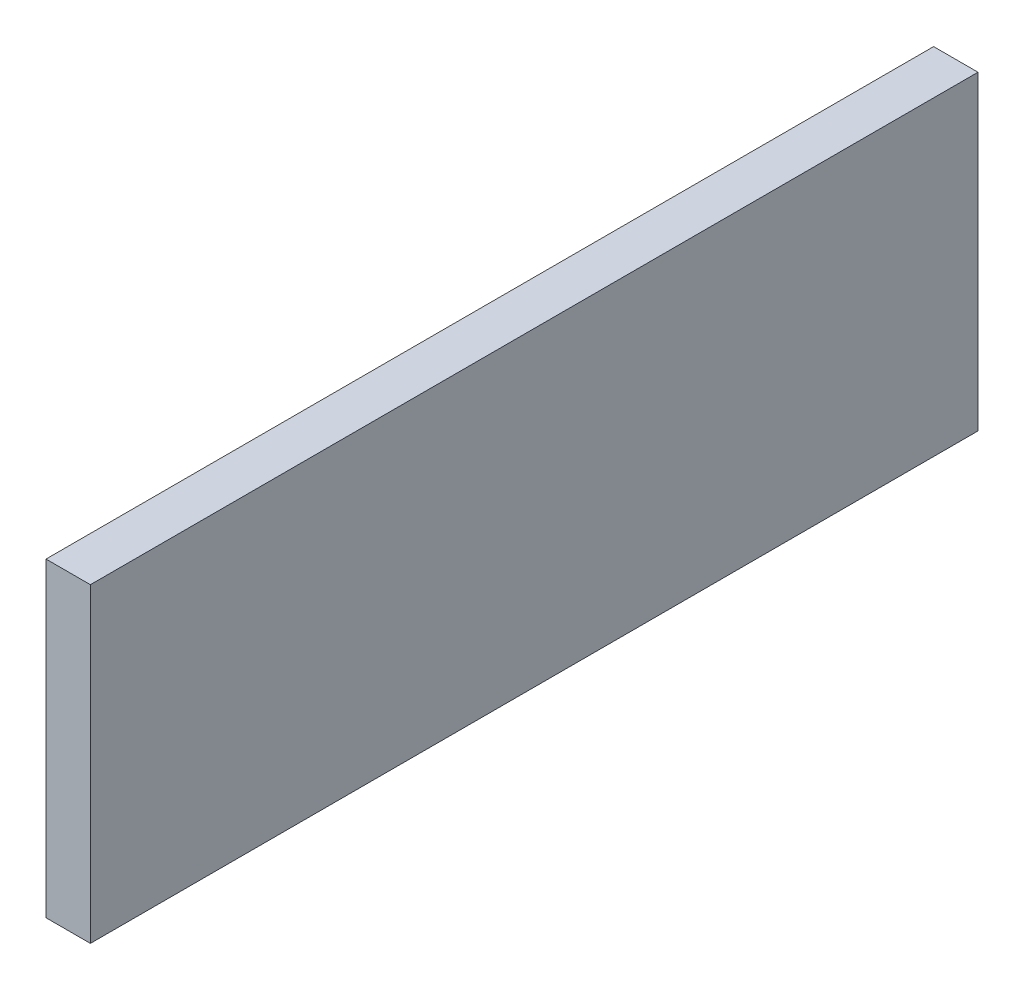
SolidWorks part; units mm, degrees
ref_plane "Front Plane" through (0, 0, 0) normal (0, 0, 1) x (1, 0, 0)
ref_plane "Top Plane" through (0, 0, 0) normal (0, 1, 0) x (1, 0, 0)
ref_plane "Right Plane" through (0, 0, 0) normal (1, 0, 0) x (0, 0, -1)
sketch "Sketch1" plane through (0, 0, 25.4) normal (0, 0, 1) x (1, 0, 0)
  line L7 (304.8, 9.525) -> (-304.8, 9.525) construction
  line L8 (304.8, 98.425) -> (292.1, 98.425)
  line L9 (304.8, 98.425) -> (304.8, 9.525)
  line L10 (304.8, 9.525) -> (292.1, 9.525)
  line L11 (292.1, 98.425) -> (292.1, 9.525)
  dimension "D1" = 12.7
extrude "Boss-Extrude1" add sketch "Sketch1" along normal blind 254
